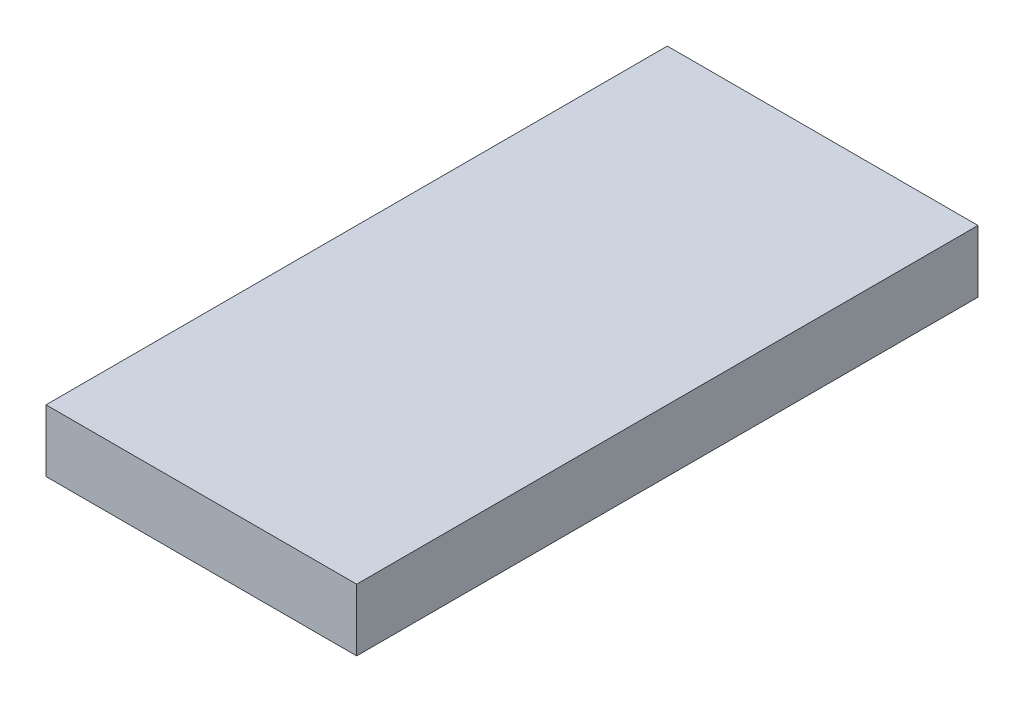
SolidWorks part; units mm, degrees
ref_plane "Alzado" through (0, 0, 0) normal (0, 0, 1) x (1, 0, 0)
ref_plane "Planta" through (0, 0, 0) normal (0, 1, 0) x (1, 0, 0)
ref_plane "Vista lateral" through (0, 0, 0) normal (1, 0, 0) x (0, 0, -1)
sketch "Croquis1" plane through (0, 0, 0) normal (0, 1, 0) x (1, 0, 0)
  line L1 (30, -60) -> (-30, -60)
  line L2 (30, -60) -> (30, 60)
  line L3 (30, 60) -> (-30, 60)
  line L4 (-30, -60) -> (-30, 60)
  line L5 (30, -60) -> (-30, 60) construction
  line L6 (30, 60) -> (-30, -60) construction
  point P0 (0, 0)
  dimension "D1" = 120
  dimension "D2" = 60
extrude "Saliente-Extruir1" add sketch "Croquis1" along normal blind 12
